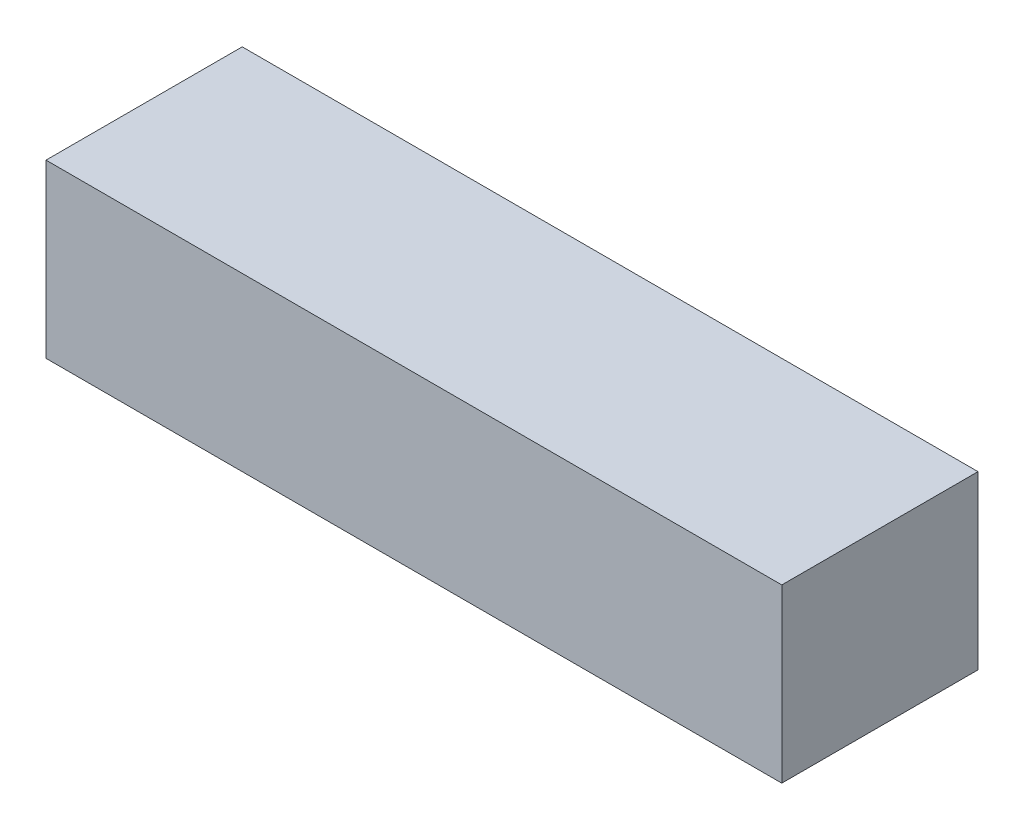
SolidWorks part; units mm, degrees
ref_plane "Front Plane" through (0, 0, 0) normal (0, 0, 1) x (1, 0, 0)
ref_plane "Top Plane" through (0, 0, 0) normal (0, 1, 0) x (1, 0, 0)
ref_plane "Right Plane" through (0, 0, 0) normal (1, 0, 0) x (0, 0, -1)
sketch "Sketch1" plane through (0, 0, 0) normal (0, 1, 0) x (1, 0, 0)
  line L1 (-75, 20) -> (75, 20)
  line L2 (-75, 20) -> (-75, -20)
  line L3 (-75, -20) -> (75, -20)
  line L4 (75, 20) -> (75, -20)
  line L5 (-75, 20) -> (75, -20) construction
  line L6 (-75, -20) -> (75, 20) construction
  point P0 (0, 0)
  dimension "D1" = 40
  dimension "D2" = 150
extrude "Boss-Extrude1" add sketch "Sketch1" along normal blind 35
